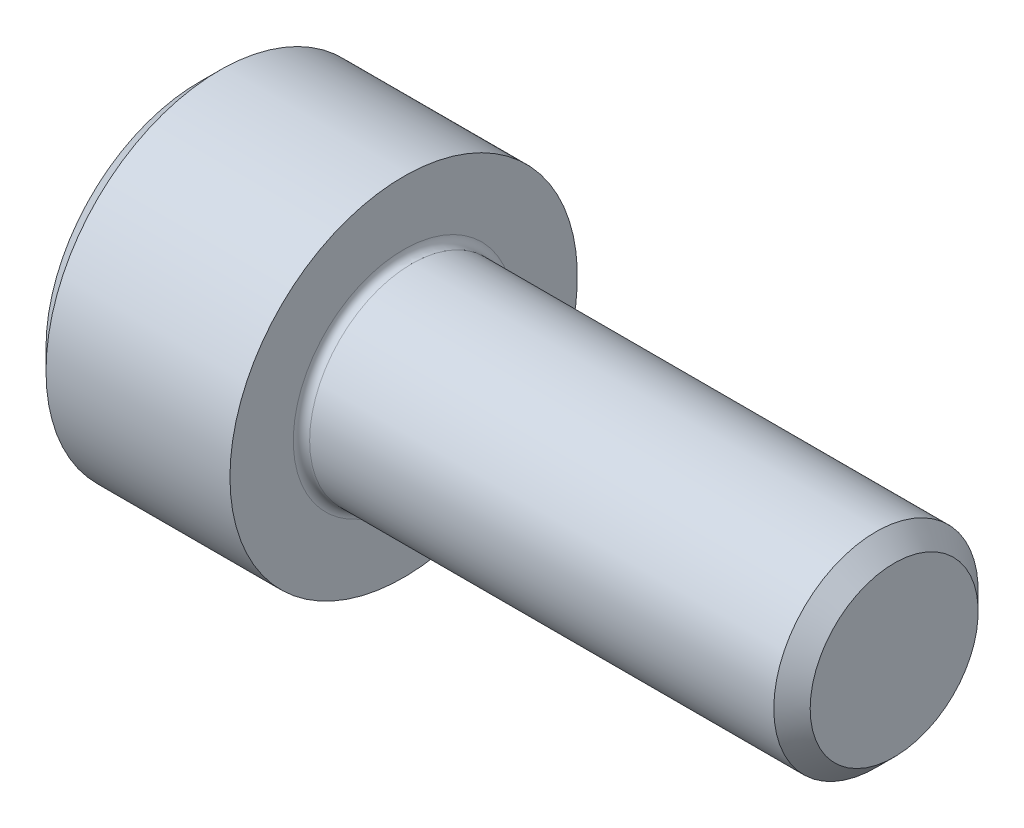
SolidWorks part; units mm, degrees
ref_plane "Plane1" through (0, 0, 0) normal (0, 0, 1) x (1, 0, 0)
ref_plane "Plane2" through (0, 0, 0) normal (0, 1, 0) x (1, 0, 0)
ref_plane "Plane3" through (0, 0, 0) normal (1, 0, 0) x (0, 0, -1)
sketch "BodySke" plane through (0, 0, 0) normal (0, 0, 1) x (1, 0, 0)
  line L0 (0, 0) -> (0, 3.75)
  line L1 (0.5, 4.25) -> (5, 4.25)
  line L2 (5, 4.25) -> (5, 2.5)
  line L3 (5, 2.5) -> (16.555, 2.5)
  line L4 (17, 2.055) -> (17, 0)
  line L5 (17, 0) -> (0, 0)
  line L6 (-31.75, 0) -> (127, 0) construction
  line L7 (0, 3.75) -> (0.5, 4.25)
  line L8 (17, 2.055) -> (16.555, 2.5)
  line L9 (0, -3.75) -> (0.5, -4.25) construction
  line L10 (17, -2.055) -> (16.555, -2.5) construction
  line L11 (5.8, 9.525) -> (5.8, 3.175) construction
  line L12 (5, 9.525) -> (5, 3.175) construction
  line L13 (-33, 9.525) -> (-33, 3.175) construction
  dimension "Diameter" = 5
  dimension "Head_ht" = 5
  dimension "Length" = 12
  dimension "Body_ch_ang" = 45
  dimension "Head_dia" = 8.5
  dimension "Head_ch_ang" = 45
  dimension "Minor_dia" = 4.11
  dimension "Advance" = 0.8
  dimension "Thread_nom" = 12
  dimension "Thread_length" = 50
  dimension "Head_ch_ht" = 0.5
revolve "Base-Revolve" add sketch "BodySke"
cosmetic thread "ThreadCosmetic" [suppressed]
fillet "Fillet1" radius 0.2 1 edges at (5, 0, 2.5)
sketch "Sketch2" plane through (0, 0, 0) normal (0, 0, 1) x (1, 0, 0)
  line L0 (0, 2.042) -> (2.5, 2.042)
  line L1 (2.5, 2.042) -> (3.6789, 0)
  line L2 (-31.75, 0) -> (127, 0) construction
  line L3 (3.6789, 0) -> (0, 0)
  line L4 (0, 0) -> (0, 2.042)
  line L5 (0, 3.75) -> (0, -3.75) construction
  line L6 (0, 0) -> (47.625, 0) construction
  line L7 (5, -4.25) -> (5, 4.25) construction
  dimension "D1" = 2.042
  dimension "D2" = 60
  dimension "Wall_thickness" = 2.5
revolve "Hex-PreBroach" cut sketch "Sketch2" angle 360 about L6
sketch "Sketch3" plane through (0, 0, 0) normal (-1, 0, 0) x (0, 0.5, 0.866)
  line L0 (1.1789, 2.042) -> (-1.1789, 2.042)
  line L1 (-1.1789, 2.042) -> (-2.3579, 0)
  line L2 (1.1789, 2.042) -> (2.3579, 0)
  line L3 (1.1789, -2.042) -> (2.3579, 0)
  line L4 (1.1789, -2.042) -> (-1.1789, -2.042)
  line L5 (-1.1789, -2.042) -> (-2.3579, 0)
  dimension "D1" = 2.042
  dimension "D2" = 2.042
  dimension "Hex_size" = 4.084
extrude "Hex" cut sketch "Sketch3" against normal blind 2.5
sketch "Sketch4" plane through (0, 0, 0) normal (-1, 0, 0) x (0, 0, 1)
  line L0 (0, 0) -> (2.3876, 0)
  line L1 (0, 0) -> (6.1484, 3.5498) construction
  line L2 (0, 0) -> (1.1938, 2.0677)
  line L3 (1.9883, 0.576) -> (2.2704, 0.7389)
  line L4 (1.493, 1.4339) -> (1.7751, 1.5968)
  arc A0 (1.9883, 0.576) -> (1.493, 1.4339) centre (0, 0) ccw
  arc A1 (2.3876, 0) -> (2.2704, 0.7389) centre (0, 0) ccw
  arc A2 (1.1938, 2.0677) -> (1.7751, 1.5968) centre (0, 0) cw
  dimension "D1" = 30
  dimension "Spline_n_dim" = 4.1402
  dimension "Spline_m_dim" = 4.7752
  dimension "D2" = 60
  dimension "D3" = 0.4953
  dimension "Spline_p_dim" = 0.9906
extrude "Spline" [suppressed] cut sketch "Sketch4" against normal blind 2.5
pattern_circular "CirPattern1" [suppressed] count 6 every 60
sketch "Sketch5" plane through (0, 0, 0) normal (0, 0, 1) x (1, 0, 0)
  line L0 (-31.75, 0) -> (127, 0) construction
  line L2 (0, 3.75) -> (0, -3.75) construction
  circle A0 centre (2, 0) radius 0.675
  dimension "Drilled_hole_dia" = 1.35
  dimension "Drilled_hole_loc" = 2
extrude "Hole" [suppressed] cut sketch "Sketch5" against normal through all and the other way through all
pattern_circular "Drilled-4" [suppressed] count 2 every 60
pattern_circular "Drilled-6" [suppressed] count 3 every 60
sketch "ThdSchSke" plane through (0, 0, 0) normal (0, 0, 1) x (1, 0, 0)
  line L0 (5.8, -2.055) -> (5.4884, -2.5)
  line L1 (5.8, -2.055) -> (6.1116, -2.5)
  line L2 (6.1116, -2.5) -> (6.1116, -3.125)
  line L3 (-3.175, 0) -> (5.1513, 0) construction
  line L5 (6.1116, -3.125) -> (5.4884, -3.125)
  line L6 (5.4884, -3.125) -> (5.4884, -2.5)
  line L7 (0, 3.75) -> (0, -3.75) construction
  dimension "Thread_minor" = 4.11
  dimension "Diameter" = 5
  dimension "Start" = 5.8
  dimension "SideAngle" = 55
  dimension "VeeAngle" = 70
  dimension "Overcut" = 6.25
revolve "ThreadSchematic" [suppressed] cut sketch "ThdSchSke" angle 360 about L3
pattern_linear "ThdSchPat" [suppressed]
equation "\"D2@Sketch3\" = \"Hex_size@Sketch3\" / 2"
equation "\"D1@Sketch3\" = \"Hex_size@Sketch3\" / 2"
equation "\"D1@Sketch2\" = \"Hex_size@Sketch3\" / 2"
equation "\"D3@Sketch4\" = \"Spline_p_dim@Sketch4\" / 2"
equation "\"Thread_minor@ThreadCosmetic\"  =  \"Minor_dia@BodySke\""
equation "\"D2@CirPattern1\" = 360 / \"Num_teeth@CirPattern1\""
equation "\"Wall_thickness@Sketch2\" = \"Head_ht@BodySke\" - \"Key_eng@Hex\""
equation "\"Thread_length@ThreadCosmetic\" = ((sgn( (\"Length@BodySke\" - \"Advance@BodySke\" ) - \"Thread_nom@BodySke\" )-1)*( (\"Length@BodySke\" - \"Advance@BodySke\" ) - \"Thread_nom@BodySke\" ))/-2+ \"Thread_nom@BodySke\""
equation "\"Thread_minor@ThdSchSke\" = \"Minor_dia@BodySke\""
equation "\"Diameter@ThdSchSke\" = \"Diameter@BodySke\""
equation "\"Overcut@ThdSchSke\" = \"Diameter@BodySke\" * 1.25"
equation "\"Start@ThdSchSke\" = \"Head_ht@BodySke\" + \"Length@BodySke\" - \"Thread_length@ThreadCosmetic\"  '---Non-countersunk---"
equation "\"Num_threads@ThdSchPat\" = int( \"Thread_length@ThreadCosmetic\" / \"Advance@BodySke\" + 0.999 )  + 1"
equation "\"Advance@ThdSchPat\" = \"Thread_length@ThreadCosmetic\" /  (\"Num_threads@ThdSchPat\" - 1) 'relax it"
equation "\"Num_threads@ThdSchPat\" = \"Num_threads@ThdSchPat\" - sgn( \"Num_threads@ThdSchPat\" - 1) '---chamfered tips only---"
